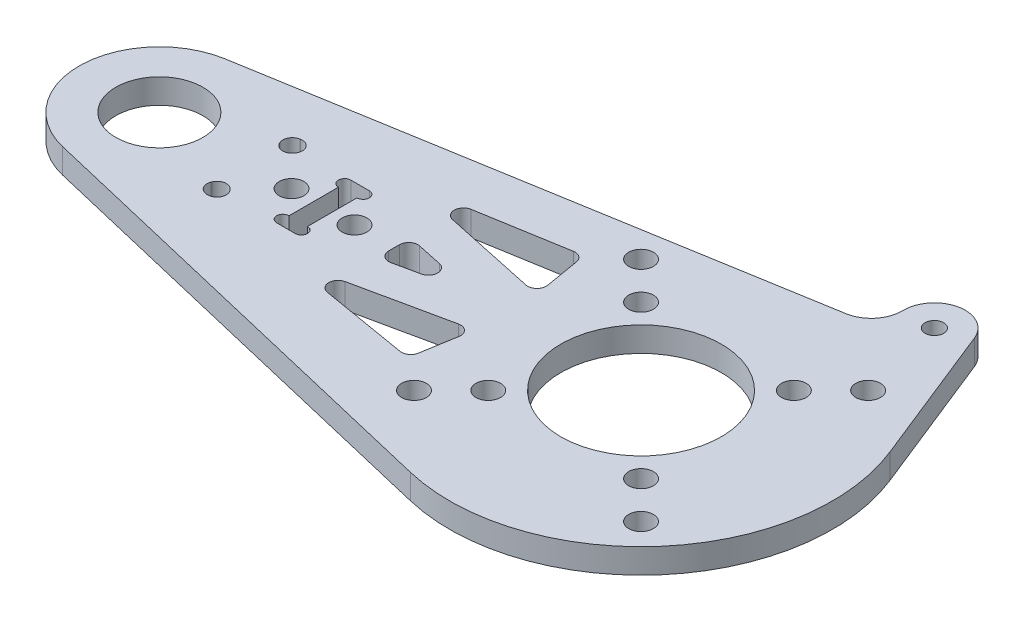
SolidWorks part; units mm, degrees
material "Thornel Mat VMA"
ref_plane "前视基准面" through (0, 0, 0) normal (0, 0, 1) x (1, 0, 0)
ref_plane "上视基准面" through (0, 0, 0) normal (0, 1, 0) x (1, 0, 0)
ref_plane "右视基准面" through (0, 0, 0) normal (1, 0, 0) x (0, 0, -1)
sketch "草图1" plane through (0, 0, 0) normal (0, 1, 0) x (1, 0, 0)
  line L0 (-80.1667, 12.8182) -> (5.8356, 27.3552)
  line L5 (-78, 0) -> (0, 0) construction
  line L6 (-81, -12.6491) -> (-7.1538, -30.1633)
  line L7 (0, 0) -> (15, 32.5) construction
  line L10 (-18.3848, 18.3848) -> (0, 0) construction
  line L11 (19.6422, 34.3575) -> (28.7815, 11.5162)
  circle A0 centre (-78, 0) radius 7.05
  arc A1 (-80.1667, 12.8182) -> (-81, -12.6491) centre (-78, 0) ccw
  arc A7 (-7.1538, -30.1633) -> (28.7815, 11.5162) centre (0, 0) ccw
  circle A8 centre (15, 32.5) radius 1.5
  circle A9 centre (0, 0) radius 26 construction
  circle A10 centre (-18.3848, 18.3848) radius 2
  circle A11 centre (18.3848, 18.3848) radius 2
  circle A12 centre (18.3848, -18.3848) radius 2
  circle A13 centre (-18.3848, -18.3848) radius 2
  arc A14 (19.6422, 34.3575) -> (10.0012, 32.3926) centre (15, 32.5) ccw
  arc A16 (5.8356, 27.3552) -> (10.0012, 32.3926) centre (5.0023, 32.2853) ccw
  circle A17 centre (0, 0) radius 17.5 construction
  circle A18 centre (-12.3744, 12.3744) radius 2
  circle A19 centre (12.3744, 12.3744) radius 2
  circle A20 centre (12.3744, -12.3744) radius 2
  circle A21 centre (-12.3744, -12.3744) radius 2
  circle A22 centre (0, 0) radius 13
  circle A23 centre (0, 0) radius 28 construction
  dimension "D3" = 14.1
  dimension "D4" = 15
  dimension "D7" = 3
  dimension "D5" = 32.5
  dimension "D6" = 26
  dimension "D2" = 52
  dimension "D10" = 5
  dimension "D12" = 5
  dimension "D13" = 4
  dimension "D14" = 4
  dimension "D15" = 35
  dimension "D16" = 2
  dimension "D17" = 5
  dimension "D18" = 26
  dimension "D1" = 78
  dimension "D8" = 4
  dimension "D9" = 45
extrude "凸台-拉伸1" add sketch "草图1" along normal blind 4
sketch "草图4" plane through (0, 4, 0) normal (0, 1, 0) x (1, 0, 0)
  line L0 (-53, 0) -> (0, 0) construction
  line L1 (-53, -6) -> (-50, -6)
  line L2 (-53, -6) -> (-53, 6)
  line L3 (-53, 6) -> (-50, 6)
  line L4 (-50, -6) -> (-50, 6)
  circle A1 centre (-78, 0) radius 7.05 construction
  circle A2 centre (-56.6, 0) radius 2
  circle A3 centre (-46.4, 0) radius 2
  dimension "D2" = 25
  dimension "D4" = 3.6
  dimension "D5" = 4
  dimension "D6" = 3.6
  dimension "D1" = 3
  dimension "D3" = 12
extrude "切除-拉伸7" cut sketch "草图4" against normal through all
sketch "草图8" plane through (0, 4, 0) normal (0, 1, 0) x (1, 0, 0)
  line L21 (-53, 6) -> (-53, -6) construction
  line L22 (-50, -6) -> (-50, 6) construction
  circle A17 centre (-53, 5) radius 1
  circle A18 centre (-53, -5) radius 1
  circle A19 centre (-50, -5) radius 1
  circle A20 centre (-50, 5) radius 1
  dimension "D1" = 2
extrude "切除-拉伸6" cut sketch "草图8" against normal through all
sketch "草图9" plane through (0, 4, 0) normal (0, 1, 0) x (1, 0, 0)
  line L0 (-23.5064, 14.282) -> (-21.9374, 5)
  line L1 (-21.9374, 5) -> (-46.8879, 10.3298)
  line L2 (-46.8879, 10.3298) -> (-23.5064, 14.282)
  line L6 (-2.2, 0) -> (2.2, 0) construction
  line L7 (-46.8879, -10.3298) -> (-23.5064, -14.282)
  line L8 (-21.9374, -5) -> (-46.8879, -10.3298)
  line L9 (-23.5064, -14.282) -> (-21.9374, -5)
  line L10 (0, 0) -> (-18.3848, 18.3848) construction
  line L11 (5.8356, 27.3552) -> (-80.1667, 12.8182) construction
  line L19 (-64.8367, 7.2959) -> (-58.6617, 8.3397)
  line L20 (-58.6617, 8.3397) -> (-63.252, 3)
  line L21 (-58.6617, -8.3397) -> (-63.252, -3)
  line L22 (-64.8367, -7.2959) -> (-58.6617, -8.3397)
  line L23 (-40, 2.7231) -> (-27.2524, 0)
  line L24 (-40, 2.7231) -> (-40, -2.7231)
  line L25 (-50, -4) -> (-50, 4) construction
  line L26 (-40, -2.7231) -> (-27.2524, 0)
  circle A0 centre (0, 0) radius 22.5 construction
  arc A1 (-63.252, 3) -> (-64.8367, 7.2959) centre (-78, 0) ccw
  circle A2 centre (-78, 0) radius 7.05 construction
  arc A3 (-63.252, -3) -> (-64.8367, -7.2959) centre (-78, 0) cw
  circle A4 centre (-56.6, 0) radius 2 construction
  circle A5 centre (-46.4, 0) radius 2 construction
  dimension "D1" = 45
  dimension "D6" = 8
  dimension "D4" = 10
  dimension "D2" = 10
  dimension "D3" = 8
  dimension "D5" = 10
  dimension "D7" = 6
  dimension "D8" = 7
  dimension "D9" = 6
extrude "切除-拉伸8" cut sketch "草图9" against normal through all
fillet "圆角1" radius 1.5 15 edges at (-21.9374, 2, -5) (-46.8879, 2, -10.3298) (-23.5064, 2, -14.282) (-58.6617, 2, 8.3397) (-63.252, 2, 3) (-23.5064, 2, 14.282) (-46.8879, 2, 10.3298) (-21.9374, 2, 5) (-58.6617, 2, -8.3397) (-63.252, 2, -3) (-64.8367, 2, -7.2959) (-64.8367, 2, 7.2959) (-27.2524, 2, 0) (-40, 2, 2.7231) (-40, 2, -2.7231)
